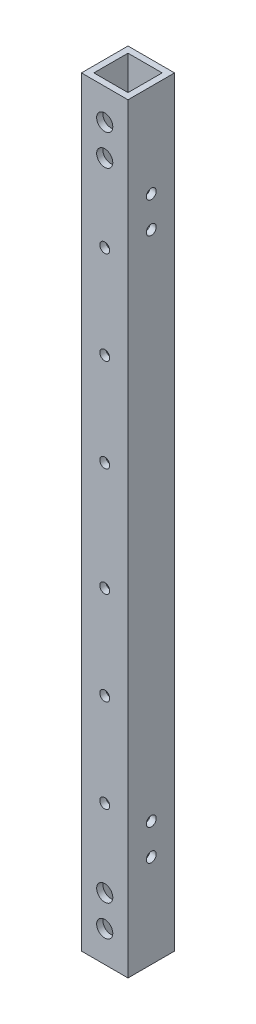
SolidWorks part; units mm, degrees
ref_plane "Front Plane" through (0, 0, 0) normal (0, 0, 1) x (1, 0, 0)
ref_plane "Top Plane" through (0, 0, 0) normal (0, 1, 0) x (1, 0, 0)
ref_plane "Right Plane" through (0, 0, 0) normal (1, 0, 0) x (0, 0, -1)
sketch "Sketch1" plane through (0, 0, 0) normal (0, 1, 0) x (1, 0, 0)
  line L0 (13, 2) -> (13, 13)
  line L1 (0, 0) -> (15, 0)
  line L2 (0, 0) -> (0, 15)
  line L3 (0, 15) -> (15, 15)
  line L4 (15, 0) -> (15, 15)
  line L5 (2, 13) -> (13, 13)
  line L6 (2, 2) -> (2, 13)
  line L7 (2, 2) -> (13, 2)
  dimension "D1" = 15
  dimension "D2" = 2
extrude "Boss-Extrude1" add sketch "Sketch1" along normal blind 245
sketch "Sketch2" plane through (15, 0, 0) normal (1, 0, 0) x (0, 0, -1)
  circle A6 centre (7.5, 215) radius 1.6
  circle A7 centre (7.5, 205) radius 1.6
  circle A8 centre (7.5, 30) radius 1.6
  circle A9 centre (7.5, 40) radius 1.6
  dimension "D1" = 3.2
extrude "Cut-Extrude1" cut sketch "Sketch2" against normal through all
sketch "Sketch4" plane through (0, 0, -15) normal (0, 0, -1) x (-1, 0, 0)
  circle A4 centre (-7.5, 235) radius 2.6
  circle A5 centre (-7.5, 225) radius 2.6
  circle A6 centre (-7.5, 10) radius 2.6
  circle A7 centre (-7.5, 20) radius 2.6
  dimension "D1" = 5.2
extrude "Cut-Extrude2" cut sketch "Sketch4" against normal through all
sketch "Sketch5" plane through (0, 0, -15) normal (0, 0, -1) x (-1, 0, 0)
  line L0 (-15, 122.5) -> (0, 122.5) construction
  line L1 (-15, 245) -> (-15, 0) construction
  line L2 (0, 245) -> (0, 0) construction
  line L3 (-7.5, 0) -> (-7.5, 245) construction
  line L4 (-15, 0) -> (0, 0) construction
  line L5 (-15, 245) -> (0, 245) construction
  circle A0 centre (-7.5, 45) radius 1.6
  circle A1 centre (-7.5, 75) radius 1.6
  circle A2 centre (-7.5, 200) radius 1.6
  circle A3 centre (-7.5, 170) radius 1.6
  circle A4 centre (-7.5, 140) radius 1.6
  circle A5 centre (-7.5, 105) radius 1.6
  dimension "D1" = 3.2
  dimension "D4" = 30
  dimension "D5" = 45
  dimension "D6" = 30
  dimension "D2" = 45
  dimension "D3" = 30
  dimension "D7" = 30
extrude "Cut-Extrude3" cut sketch "Sketch5" against normal through all
